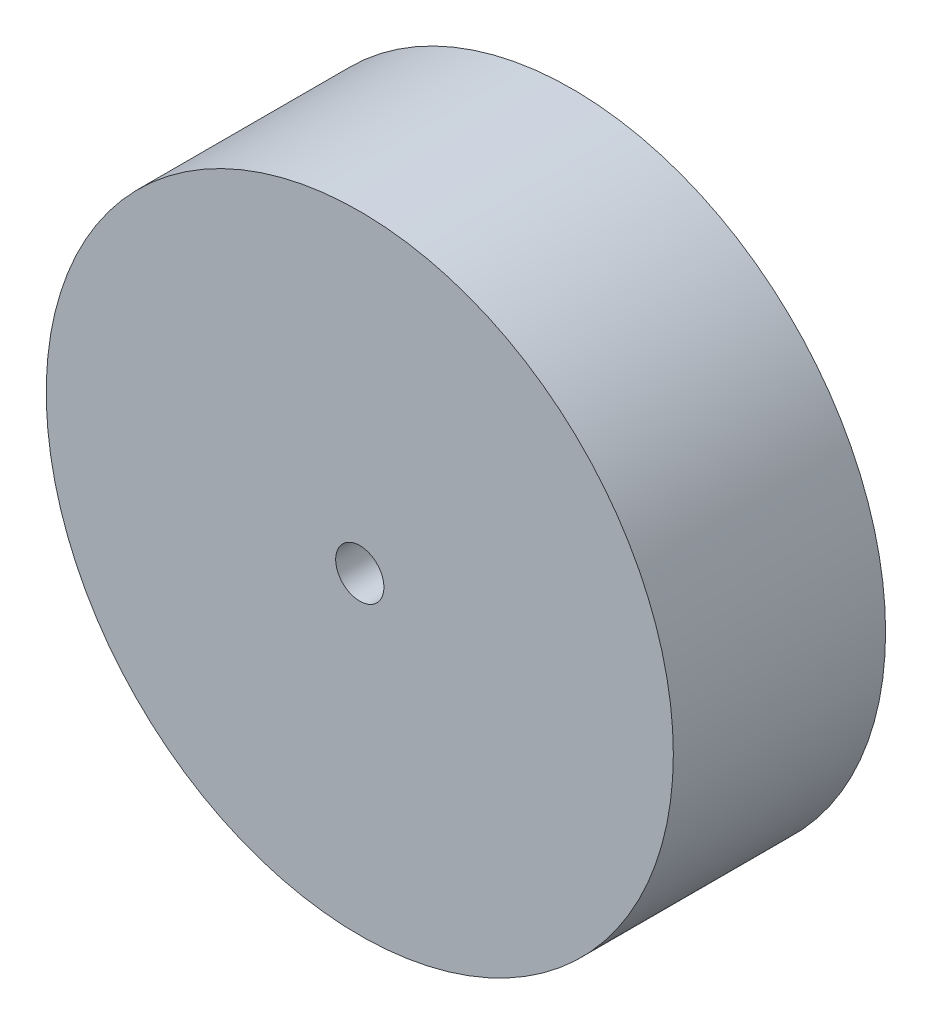
SolidWorks part; units mm, degrees
material "Rubber"
ref_plane "Front Plane" through (0, 0, 0) normal (0, 0, 1) x (1, 0, 0)
ref_plane "Top Plane" through (0, 0, 0) normal (0, 1, 0) x (1, 0, 0)
ref_plane "Right Plane" through (0, 0, 0) normal (1, 0, 0) x (0, 0, -1)
sketch "Sketch1" plane through (0, 0, 0) normal (0, 0, 1) x (1, 0, 0)
  circle A0 centre (0, 0) radius 32.5
  circle A1 centre (0, 0) radius 2.5
  dimension "D1" = 65
  dimension "D2" = 5
extrude "Boss-Extrude1" add sketch "Sketch1" along normal blind 22
